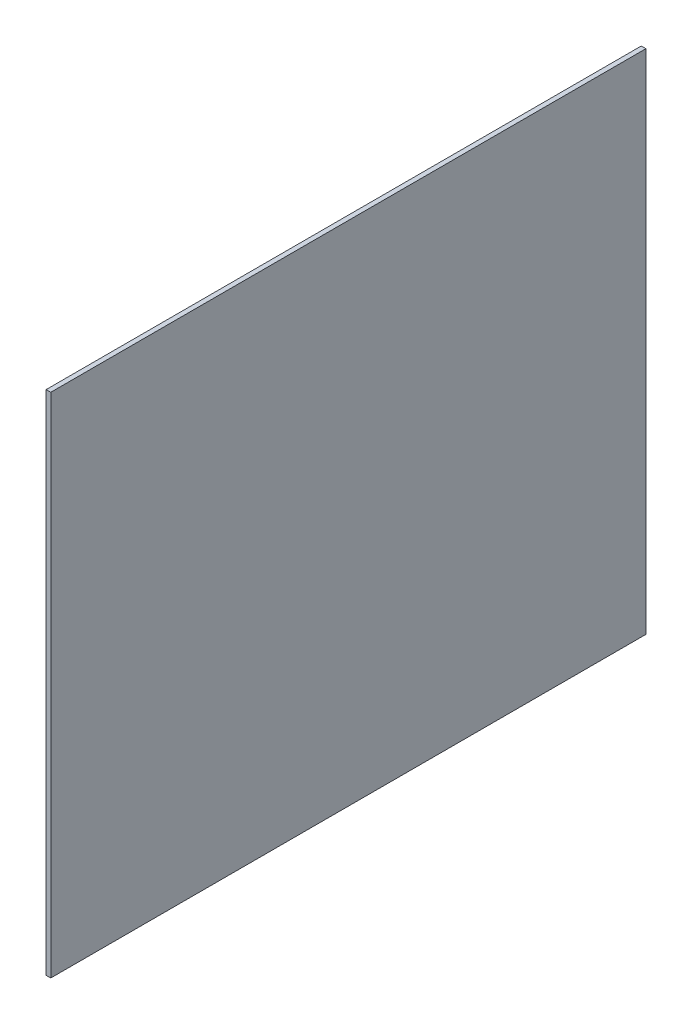
SolidWorks part; units mm, degrees
material "Pine"
ref_plane "Front Plane" through (0, 0, 0) normal (0, 0, 1) x (1, 0, 0)
ref_plane "Top Plane" through (0, 0, 0) normal (0, 1, 0) x (1, 0, 0)
ref_plane "Right Plane" through (0, 0, 0) normal (1, 0, 0) x (0, 0, -1)
sketch "Sketch1" plane through (0, 0, 0) normal (0, 0, 1) x (1, 0, 0)
  line L1 (-41.8022, 637.6309) -> (-35.4522, 637.6309)
  line L2 (-41.8022, 637.6309) -> (-41.8022, -54.5191)
  line L3 (-41.8022, -54.5191) -> (-35.4522, -54.5191)
  line L4 (-35.4522, 637.6309) -> (-35.4522, -54.5191)
extrude "Boss-Extrude1" add sketch "Sketch1" along normal blind 812.0075
